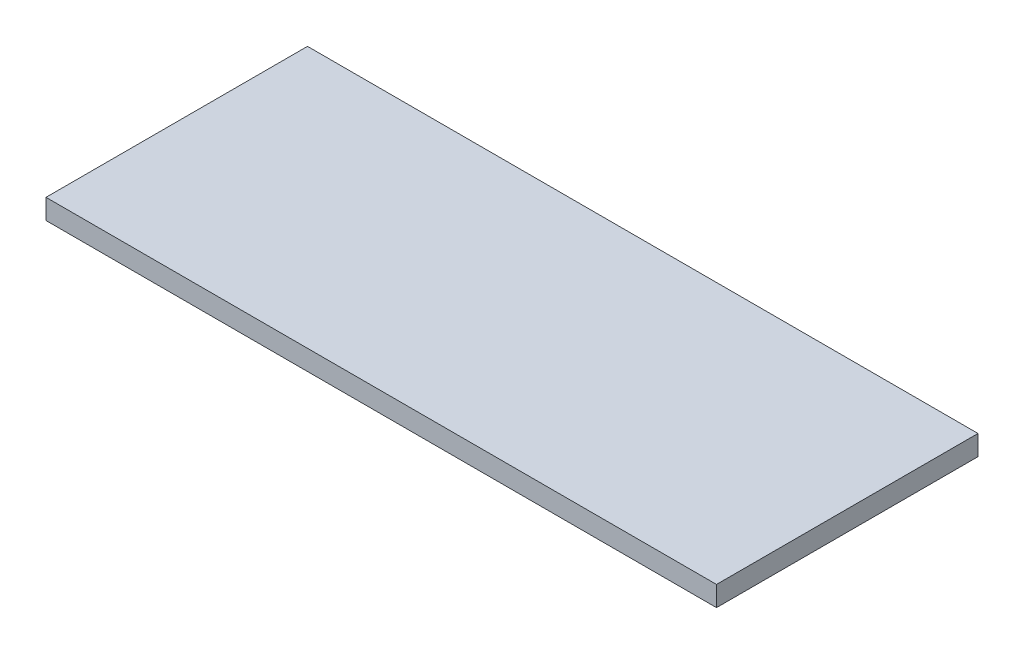
SolidWorks part; units mm, degrees
ref_plane "前视基准面" through (0, 0, 0) normal (0, 0, 1) x (1, 0, 0)
ref_plane "上视基准面" through (0, 0, 0) normal (0, 1, 0) x (1, 0, 0)
ref_plane "右视基准面" through (0, 0, 0) normal (1, 0, 0) x (0, 0, -1)
sketch "草图1" plane through (0, 0, 0) normal (0, 1, 0) x (1, 0, 0)
  line L1 (-48.7973, 24.7218) -> (51.2027, 24.7218)
  line L2 (-48.7973, 24.7218) -> (-48.7973, -14.2782)
  line L3 (-48.7973, -14.2782) -> (51.2027, -14.2782)
  line L4 (51.2027, 24.7218) -> (51.2027, -14.2782)
  dimension "D1" = 100
  dimension "D2" = 39
extrude "凸台-拉伸1" add sketch "草图1" along normal blind 3 contours L2 L3 L4 L1
